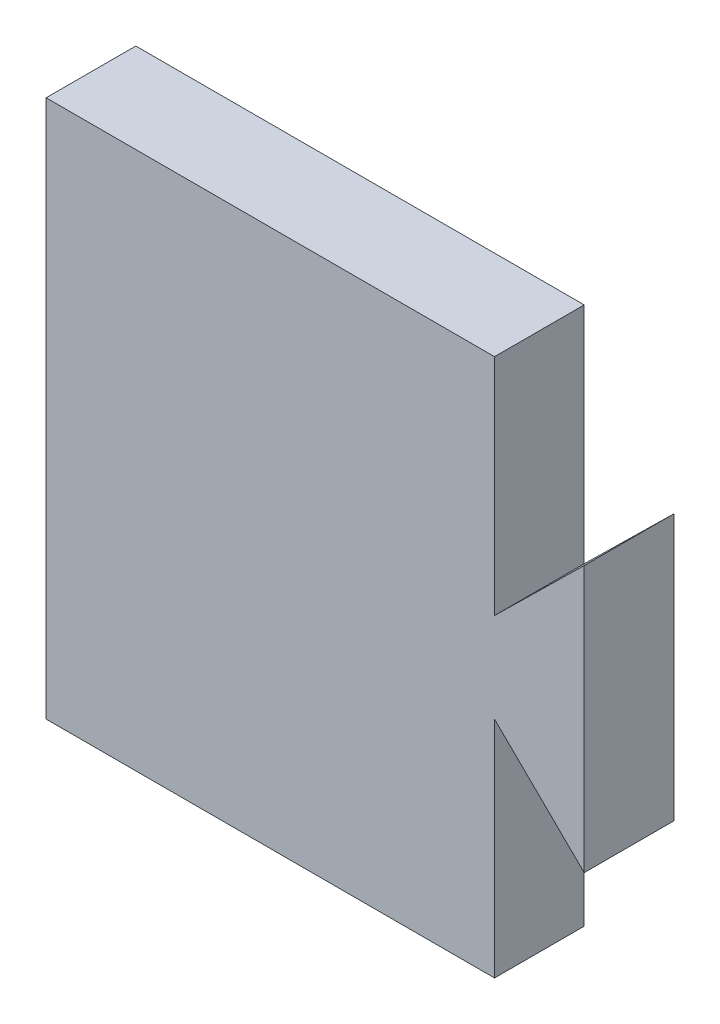
SolidWorks part; units mm, degrees
ref_plane "前视基准面" through (0, 0, 0) normal (0, 0, 1) x (1, 0, 0)
ref_plane "上视基准面" through (0, 0, 0) normal (0, 1, 0) x (1, 0, 0)
ref_plane "右视基准面" through (0, 0, 0) normal (1, 0, 0) x (0, 0, -1)
sketch "草图2" plane through (0, 0, 0) normal (0, 0, 1) x (1, 0, 0)
  line L0 (-42.7869, 15.9836) -> (7.2131, 15.9836)
  line L1 (-42.7869, 15.9836) -> (-42.7869, -44.0164)
  line L2 (7.2131, 15.9836) -> (7.2131, -44.0164)
  line L3 (-42.7869, -44.0164) -> (7.2131, -44.0164)
  dimension "D1" = 50
  dimension "D2" = 60
extrude "凸台-拉伸1" add sketch "草图2" along normal blind 10
sketch "草图4" plane through (0, 0, 10) normal (0, 0, 1) x (1, 0, 0)
  line L0 (7.2131, -9.0164) -> (17.2131, -9.0164)
  line L1 (7.2131, -9.0164) -> (7.2131, -19.0164)
  line L2 (17.2131, -9.0164) -> (17.2131, -19.0164)
  line L3 (7.2131, -19.0164) -> (17.2131, -19.0164)
  line L4 (7.2131, -44.0164) -> (7.2131, 15.9836) construction
  dimension "D1" = 25
  dimension "D2" = 25
  dimension "D3" = 10
extrude "凸台-拉伸2" add sketch "草图4" against normal blind 10
sketch "草图5" plane through (0, 0, 10) normal (0, 0, 1) x (1, 0, 0)
  line L0 (7.2131, -9.0164) -> (17.2131, 0.8106)
  line L1 (17.2131, 0.8106) -> (17.2131, -9.0164)
  line L2 (17.2131, -9.0164) -> (7.2131, -9.0164)
  line L3 (7.2131, -19.0164) -> (17.2131, -19.0164)
  line L4 (17.2131, -19.0164) -> (17.2131, -28.8434)
  line L5 (17.2131, -28.8434) -> (7.2131, -19.0164)
  dimension "D1" = 44.5
  dimension "D2" = 44.5
extrude "凸台-拉伸3" add sketch "草图5" against normal blind 10
